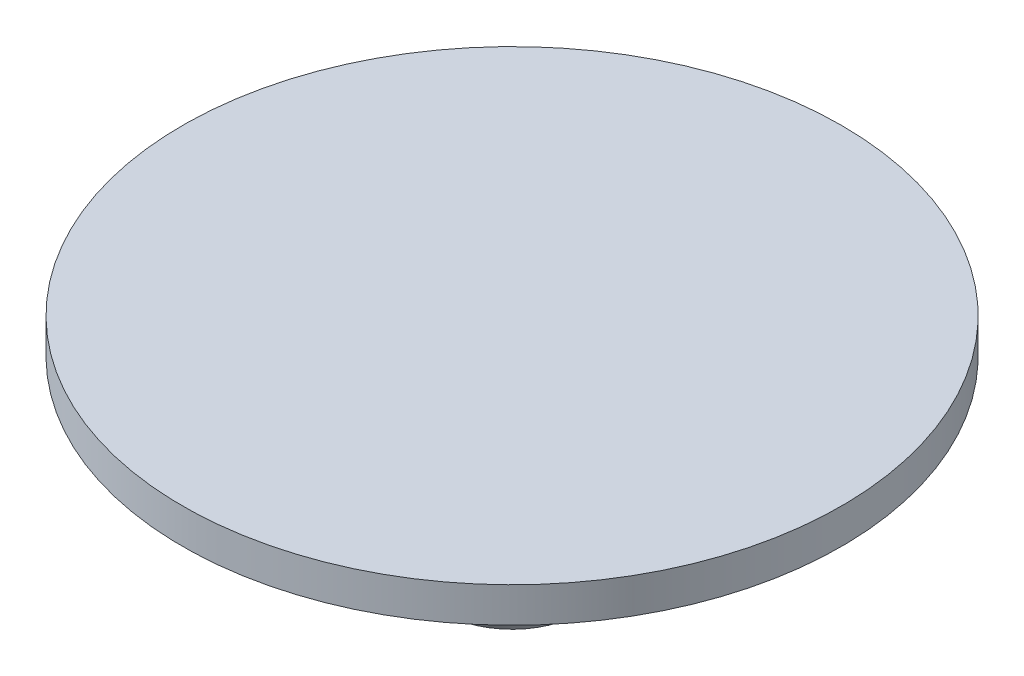
SolidWorks part; units mm, degrees
material "6061 Alloy"
ref_plane "Front Plane" through (0, 0, 0) normal (0, 0, 1) x (1, 0, 0)
ref_plane "Top Plane" through (0, 0, 0) normal (0, 1, 0) x (1, 0, 0)
ref_plane "Right Plane" through (0, 0, 0) normal (1, 0, 0) x (0, 0, -1)
sketch "Sketch1" plane through (0, 0, 0) normal (0, 0, 1) x (1, 0, 0)
  line L0 (0, 0) -> (14.1, 0)
  line L1 (0, -55) -> (0, 55) construction
  line L2 (14.1, 0) -> (14.1, -1.5)
  line L3 (14.1, -1.5) -> (6.85, -1.5)
  line L4 (6.85, -1.5) -> (3, -9.5)
  line L5 (3, -9.5) -> (2, -9.5)
  line L6 (2, -9.5) -> (2, -1.5)
  line L7 (2, -1.5) -> (0, -1.5)
  line L8 (0, -1.5) -> (0, 0)
  line L9 (55, 0) -> (-55, 0) construction
  dimension "D1" = 1.5
  dimension "D2" = 6.85
  dimension "D3" = 14.1
  dimension "D4" = 9.5
  dimension "D5" = 3
  dimension "D6" = 2
revolve "Revolve1" add sketch "Sketch1" angle 360 about L8
sketch "Sketch2" plane through (0, 0, 0) normal (0, 0, 1) x (1, 0, 0)
  line L0 (0, -5.225) -> (0, 5.225) construction
  line L1 (-14.1, -1.5) -> (14.1, -1.5) construction
  circle A0 centre (0, -5.6) radius 1.25
  dimension "D2" = 2.5
  dimension "D1" = 4.1
extrude "Cut-Extrude1" cut sketch "Sketch2" against normal blind 10
